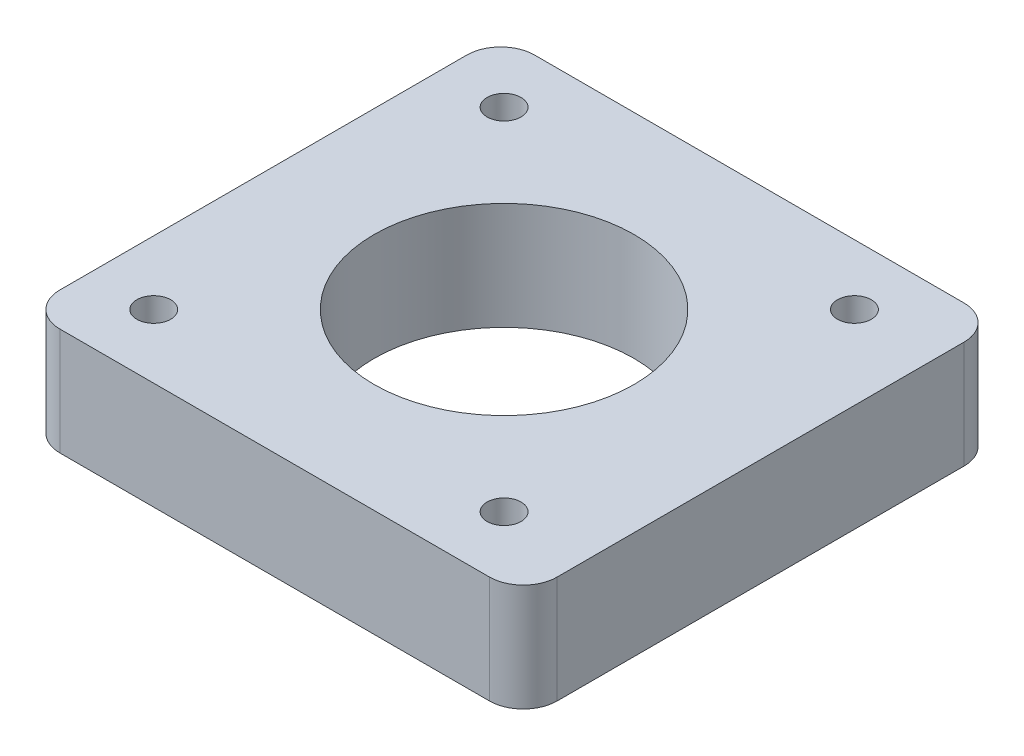
SolidWorks part; units mm, degrees
ref_plane "前视基准面" through (0, 0, 0) normal (0, 0, 1) x (1, 0, 0)
ref_plane "上视基准面" through (0, 0, 0) normal (0, 1, 0) x (1, 0, 0)
ref_plane "右视基准面" through (0, 0, 0) normal (1, 0, 0) x (0, 0, -1)
sketch "草图1" plane through (0, 0, 0) normal (0, 1, 0) x (1, 0, 0)
  line L1 (0, 0) -> (44, 0)
  line L2 (0, 0) -> (0, -42)
  line L3 (0, -42) -> (44, -42)
  line L4 (44, 0) -> (44, -42)
  dimension "D1" = 42
  dimension "D2" = 44
extrude "凸台-拉伸1" add sketch "草图1" along normal blind 9.5
sketch "草图2" plane through (0, 9.5, 0) normal (0, 1, 0) x (1, 0, 0)
  circle A0 centre (21.15, -20.85) radius 11.5
  dimension "D1" = 23
extrude "切除-拉伸1" cut sketch "草图2" against normal through all
fillet "圆角1" radius 3 4 edges at (44, 4.75, 0) (0, 4.75, 0) (0, 4.75, 42) (44, 4.75, 42)
sketch "草图5" plane through (0, 0, 0) normal (0, -1, 0) x (1, 0, 0)
  circle A0 centre (36.65, 36.35) radius 1.5
  circle A1 centre (5.65, 36.35) radius 1.5
  circle A2 centre (5.65, 5.35) radius 1.5
  circle A3 centre (36.65, 5.35) radius 1.5
  dimension "D1" = 3
extrude "切除-拉伸2" cut sketch "草图5" against normal through all
